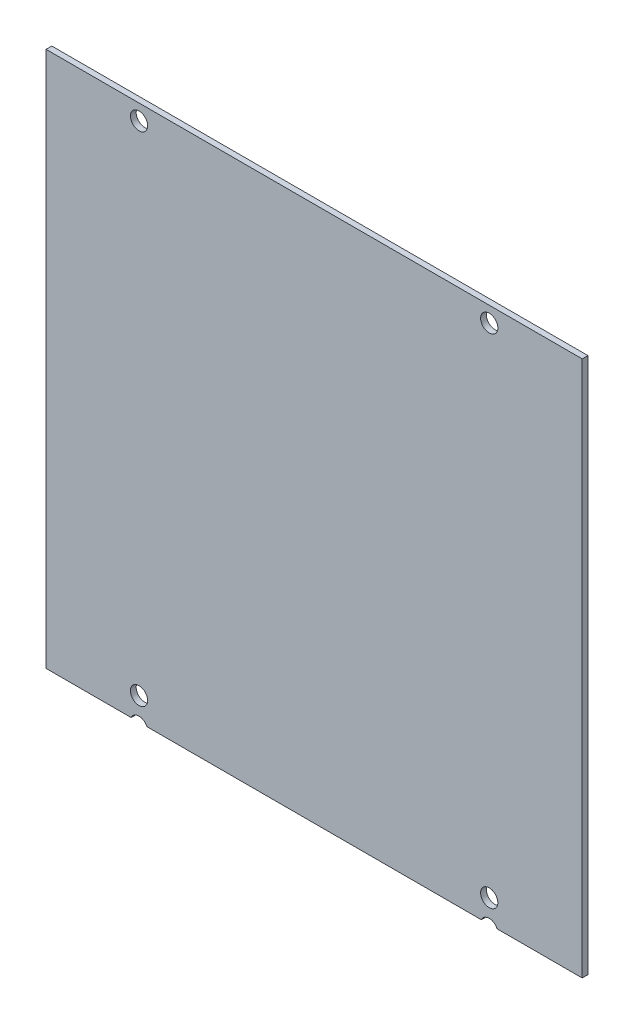
SolidWorks part; units mm, degrees
material "6061 Сплав"
ref_plane "Front Plane" through (0, 0, 0) normal (0, 0, 1) x (1, 0, 0)
ref_plane "Top Plane" through (0, 0, 0) normal (0, 1, 0) x (1, 0, 0)
ref_plane "Right Plane" through (0, 0, 0) normal (1, 0, 0) x (0, 0, -1)
sketch "Sketch1" plane through (0, 0, 0) normal (0, 0, 1) x (1, 0, 0)
  line L1 (46.7, -46.7) -> (-46.7, -46.7)
  line L2 (46.7, -46.7) -> (46.7, 46.7)
  line L3 (46.7, 46.7) -> (-46.7, 46.7)
  line L4 (-46.7, -46.7) -> (-46.7, 46.7)
  line L5 (46.7, -46.7) -> (-46.7, 46.7) construction
  line L6 (46.7, 46.7) -> (-46.7, -46.7) construction
  point P0 (0, 0)
  dimension "D1" = 93.4
  dimension "D2" = 93.4
extrude "Boss-Extrude1" add sketch "Sketch1" along normal blind 1
hole_wizard "Ø3.0 (3) Diameter Hole1" positions "Sketch3" profile "Sketch2" hole size "Ø3.0" standard "ANSI Metric"
sketch "Sketch3" plane through (0, 0, 1) normal (0, 0, 1) x (1, 0, 0)
  line L6 (-46.7, -46.7) -> (46.7, -46.7) construction
  line L9 (46.7, 46.7) -> (-46.7, 46.7) construction
  line L10 (0, 46.7) -> (0, 163.7587) construction
  line L11 (0, 46.7) -> (0, -152.1509) construction
  point P0 (-30.5, -47.3)
  point P2 (30.5, -47.3)
  point P15 (30.5, -42.7)
  point P17 (-30.5, -42.7)
  point P54 (-30.5, 44)
  point P56 (30.5, 44)
  point P58 (-30.5, -66)
  point P60 (30.5, -66)
  dimension "D2" = 4
  dimension "D3" = 2.7
  dimension "D4" = 4
  dimension "D5" = 30.5
  dimension "D6" = 30.5
  dimension "D7" = 94
  dimension "D8" = 30.5
  dimension "D9" = 2.7
  dimension "D10" = 94
  dimension "D11" = 30.5
  dimension "D12" = 30.5
  dimension "D13" = 30.5
  dimension "D14" = 30.5
  dimension "D15" = 30.5
  dimension "D16" = 112.7
  dimension "D17" = 112.7
sketch "Sketch2" plane through (-30.5, -47.3, 1) normal (1, 0, 0) x (0, -1, 0)
  line L0 (0, 0) -> (0, 1)
  line L1 (0, 1) -> (1.5, 1)
  line L2 (1.5, 1) -> (1.5, 0)
  line L5 (1.5, 0) -> (0, 0)
  line L10 (0, 1) -> (-1.5, 1) construction
  line L11 (0, -6.35) -> (0, 107.95) construction
  dimension "Hole Dia." = 3
  dimension "Hole Depth" = 1
  dimension "Drill Angle" = 180
